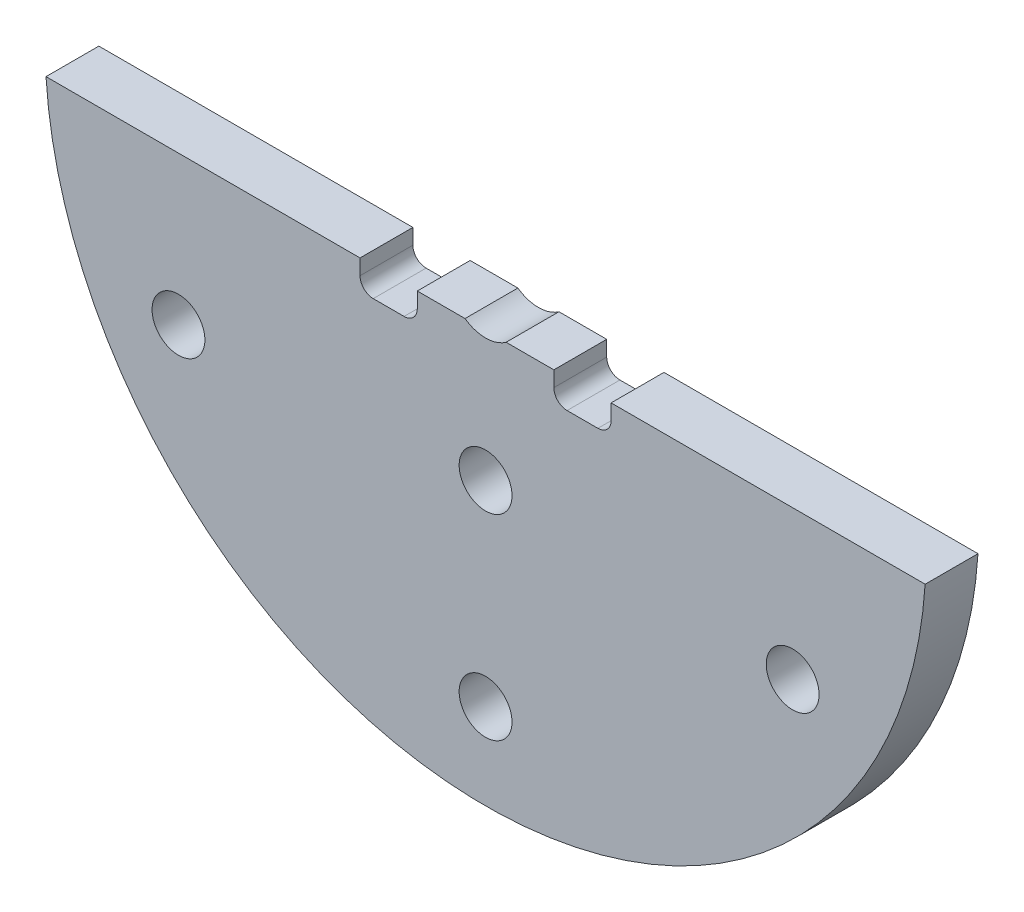
SolidWorks part; units mm, degrees
ref_plane "Alzado" through (0, 0, 0) normal (0, 0, 1) x (1, 0, 0)
ref_plane "Planta" through (0, 0, 0) normal (0, 1, 0) x (1, 0, 0)
ref_plane "Vista lateral" through (0, 0, 0) normal (1, 0, 0) x (0, 0, -1)
sketch "Model" plane through (0, 0, 0) normal (0, 0, 1) x (1, 0, 0)
  line L0 (191.3969, 188.9643) -> (194.1059, 188.9643)
  line L1 (186.3559, 188.9643) -> (189.065, 188.9643)
  line L2 (185.6059, 187.3393) -> (183.8559, 187.3393)
  line L3 (186.3559, 188.9643) -> (186.3559, 188.0893)
  line L4 (197.3559, 188.0893) -> (197.3559, 188.9643)
  line L5 (194.8559, 187.3393) -> (196.6059, 187.3393)
  line L6 (194.1059, 188.9643) -> (194.1059, 188.0893)
  line L7 (165.2838, 188.9643) -> (183.1059, 188.9643)
  line L8 (197.3559, 188.9643) -> (215.1781, 188.9643)
  line L9 (183.1059, 188.0893) -> (183.1059, 188.9643)
  arc A0 (165.2838, 188.9643) -> (193.4809, 165.8014) centre (190.2309, 190.5893) ccw
  arc A1 (193.4809, 165.8014) -> (215.1781, 188.9643) centre (190.2309, 190.5893) ccw
  arc A2 (189.065, 188.9643) -> (191.3969, 188.9643) centre (190.2309, 190.5893) ccw
  circle A3 centre (172.8025, 180.527) radius 1.5
  circle A4 centre (190.2309, 170.4647) radius 1.5
  circle A5 centre (207.6594, 180.527) radius 1.5
  arc A6 (183.1059, 188.0893) -> (183.8559, 187.3393) centre (183.8559, 188.0893) ccw
  arc A7 (185.6059, 187.3393) -> (186.3559, 188.0893) centre (185.6059, 188.0893) ccw
  arc A8 (196.6059, 187.3393) -> (197.3559, 188.0893) centre (196.6059, 188.0893) ccw
  arc A9 (194.1059, 188.0893) -> (194.8559, 187.3393) centre (194.8559, 188.0893) ccw
  circle A10 centre (190.2309, 181.5893) radius 1.5
extrude "Saliente-Extruir1" add sketch "Model" along normal blind 3
